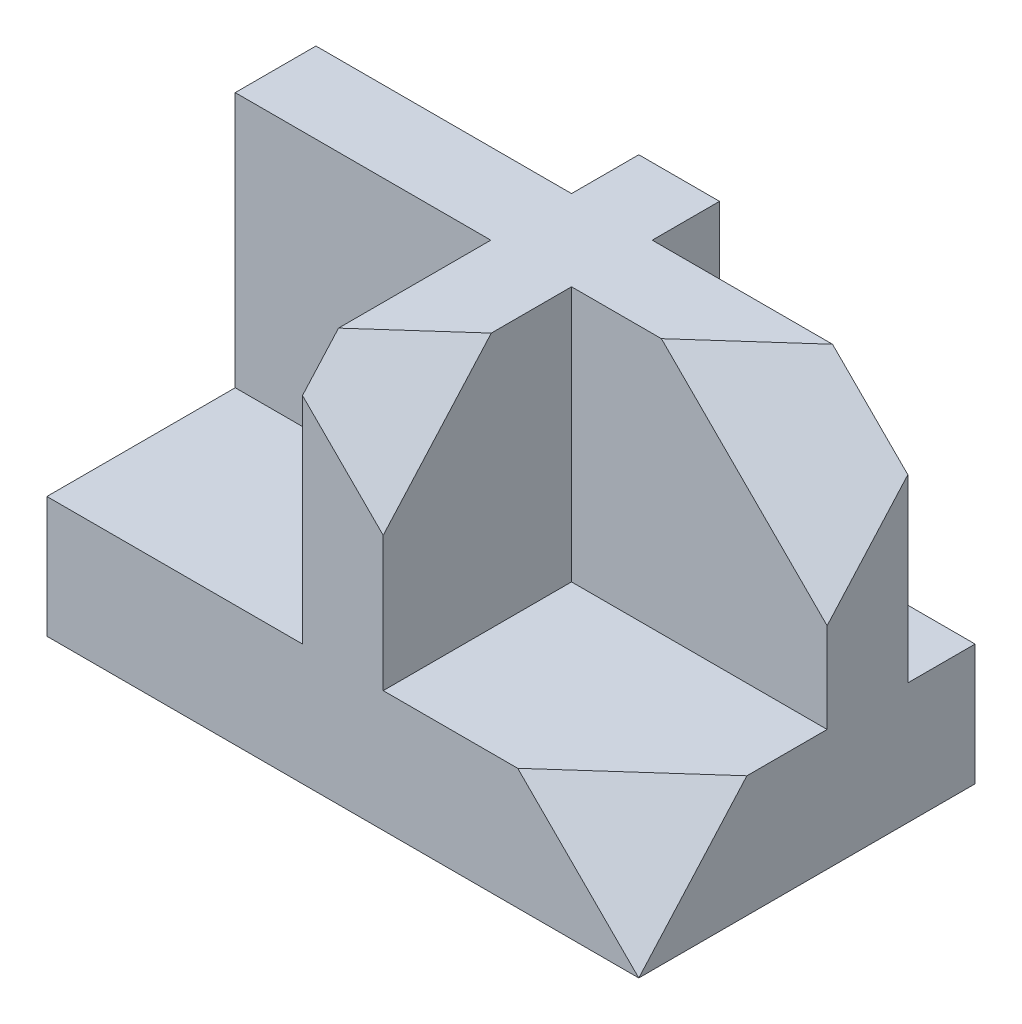
SolidWorks part; units mm, degrees
ref_plane "Front Plane" through (0, 0, 0) normal (0, 0, 1) x (1, 0, 0)
ref_plane "Top Plane" through (0, 0, 0) normal (0, 1, 0) x (1, 0, 0)
ref_plane "Right Plane" through (0, 0, 0) normal (1, 0, 0) x (0, 0, -1)
sketch "Sketch1" plane through (0, 0, 0) normal (0, 1, 0) x (1, 0, 0)
  line L1 (0, 0) -> (88, 0)
  line L2 (0, 0) -> (0, 50)
  line L3 (0, 50) -> (88, 50)
  line L4 (88, 0) -> (88, 50)
  dimension "D1" = 88
  dimension "D2" = 50
extrude "Boss-Extrude1" add sketch "Sketch1" along normal blind 18
sketch "Sketch2" plane through (0, 18, 0) normal (0, 1, 0) x (1, 0, 0)
  line L0 (88, 50) -> (0, 50) construction
  line L1 (38, 50) -> (50, 50)
  line L2 (38, 50) -> (38, 40)
  line L3 (38, 0) -> (50, 0)
  line L4 (50, 50) -> (50, 40)
  line L5 (0, 0) -> (88, 0) construction
  line L6 (0, 50) -> (0, 0) construction
  line L7 (88, 0) -> (88, 50) construction
  line L8 (0, 40) -> (38, 40)
  line L9 (0, 40) -> (0, 28)
  line L10 (0, 28) -> (38, 28)
  line L11 (88, 40) -> (88, 28)
  line L12 (50, 40) -> (88, 40)
  line L13 (38, 28) -> (38, 0)
  line L14 (50, 28) -> (88, 28)
  line L15 (50, 28) -> (50, 0)
  dimension "D1" = 12
  dimension "D2" = 38
  dimension "D3" = 12
  dimension "D4" = 28
extrude "Boss-Extrude2" add sketch "Sketch2" along normal blind 38
ref_point "Point1"
sketch "Sketch4" plane through (0, 0, 0) normal (0, 0, 1) x (1, 0, 0)
  line L0 (88, 0) -> (30.9896, 57.0104) construction
  line L1 (0, 0) -> (88, 0) construction
  line L2 (0, 56) -> (38, 56) construction
  point P5 (32, 56)
  dimension "D1" = 45
ref_plane "Plane1" through (27.0403, 27.0403, 30.2852) normal (-0.5543, -0.5543, -0.6208) x (-0.8323, 0.3692, 0.4135)
sketch "Sketch5" plane through (27.0403, 27.0403, 30.2852) normal (-0.5543, -0.5543, -0.6208) x (-0.8323, 0.3692, 0.4135)
  line L1 (-4.083, 75.5549) -> (-88.479, 75.5549)
  line L2 (-4.083, 75.5549) -> (-4.083, -12.7297)
  line L3 (-4.083, -12.7297) -> (-88.479, -12.7297)
  line L4 (-88.479, 75.5549) -> (-88.479, -12.7297)
extrude "Cut-Extrude1" cut sketch "Sketch5" against normal blind 38
